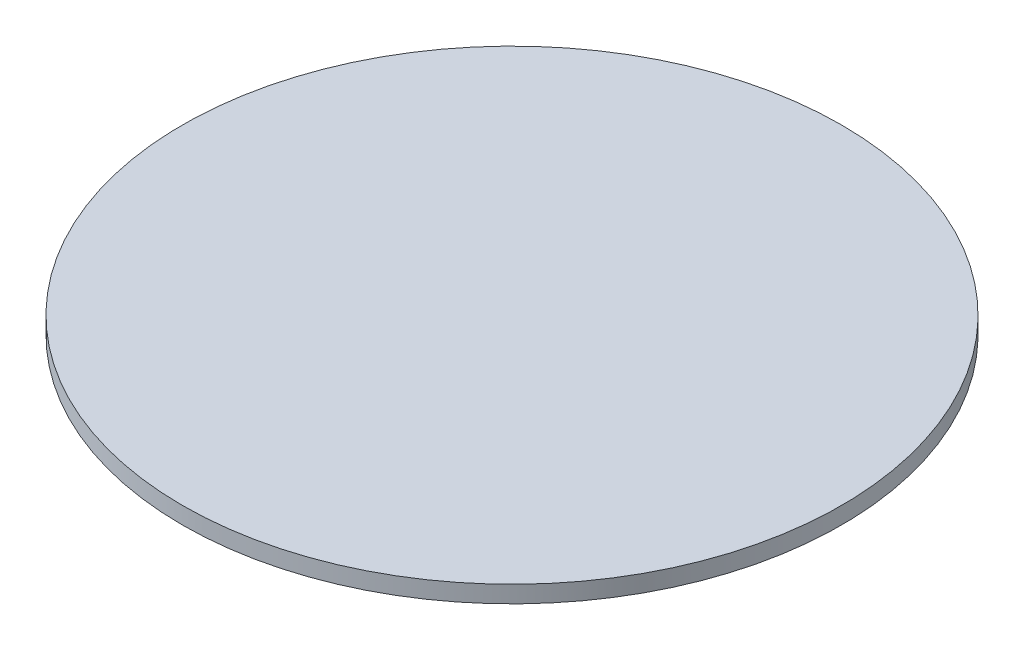
SolidWorks part; units mm, degrees
ref_plane "Front Plane" through (0, 0, 0) normal (0, 0, 1) x (1, 0, 0)
ref_plane "Top Plane" through (0, 0, 0) normal (0, 1, 0) x (1, 0, 0)
ref_plane "Right Plane" through (0, 0, 0) normal (1, 0, 0) x (0, 0, -1)
sketch "Sketch1" plane through (0, 0, 0) normal (0, 1, 0) x (1, 0, 0)
  circle A0 centre (0, 0) radius 38.8
extrude "Boss-Extrude1" add sketch "Sketch1" along normal blind 2
